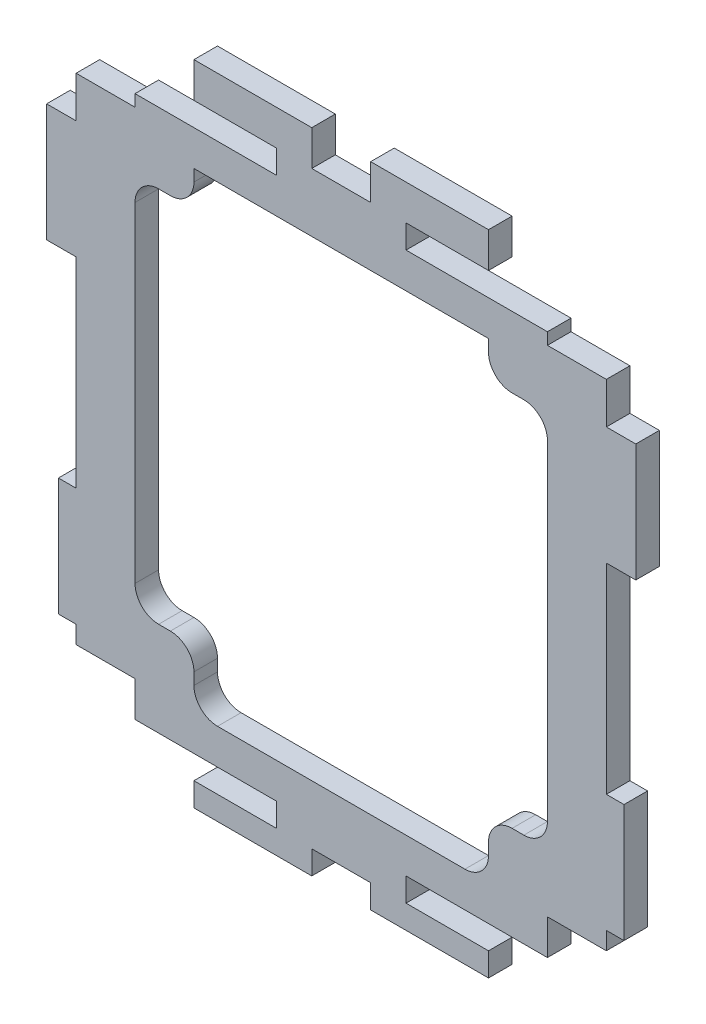
SolidWorks part; units mm, degrees
ref_plane "前视基准面" through (0, 0, 0) normal (0, 0, 1) x (1, 0, 0)
ref_plane "上视基准面" through (0, 0, 0) normal (0, 1, 0) x (1, 0, 0)
ref_plane "右视基准面" through (0, 0, 0) normal (1, 0, 0) x (0, 0, -1)
sketch "Model" plane through (0, 0, 0) normal (0, 0, 1) x (1, 0, 0)
  line L0 (1277.9121, 487.0806) -> (1277.9121, 483.5806)
  line L1 (1277.9121, 446.5806) -> (1277.9121, 445.0806)
  line L2 (1277.9121, 456.5806) -> (1276.4121, 456.5806)
  line L3 (1277.9121, 446.5806) -> (1276.4121, 446.5806)
  line L4 (1277.9121, 445.0806) -> (1282.9121, 445.0806)
  line L5 (1282.9121, 445.0806) -> (1282.9121, 442.0806)
  line L6 (1277.9121, 456.5806) -> (1277.9121, 473.5806)
  line L7 (1277.9121, 487.0806) -> (1282.9121, 487.0806)
  line L8 (1282.9121, 487.0806) -> (1282.9121, 488.0806)
  line L9 (1276.4121, 456.5806) -> (1276.4121, 446.5806)
  line L10 (1302.9121, 490.0806) -> (1297.9121, 490.0806)
  line L11 (1297.9121, 493.0806) -> (1287.9121, 493.0806)
  line L12 (1287.9121, 490.0806) -> (1287.9121, 493.0806)
  line L13 (1297.9121, 493.0806) -> (1297.9121, 490.0806)
  line L14 (1297.9121, 438.0806) -> (1287.9121, 438.0806)
  line L15 (1287.9121, 440.0806) -> (1287.9121, 438.0806)
  line L16 (1297.9121, 438.0806) -> (1297.9121, 440.0806)
  line L17 (1284.9121, 482.0806) -> (1285.9121, 482.0806)
  line L18 (1287.9121, 484.0806) -> (1287.9121, 485.0806)
  line L19 (1284.9121, 450.0806) -> (1285.9121, 450.0806)
  line L20 (1287.9121, 448.0806) -> (1287.9121, 447.0806)
  line L21 (1289.9121, 445.0806) -> (1310.9121, 445.0806)
  line L22 (1322.9121, 487.0806) -> (1322.9121, 483.5806)
  line L23 (1322.9121, 473.5806) -> (1322.9121, 456.5806)
  line L24 (1322.9121, 473.5806) -> (1325.4121, 473.5806)
  line L25 (1322.9121, 483.5806) -> (1325.4121, 483.5806)
  line L26 (1322.9121, 456.5806) -> (1324.4121, 456.5806)
  line L27 (1322.9121, 446.5806) -> (1324.4121, 446.5806)
  line L28 (1322.9121, 445.0806) -> (1317.9121, 445.0806)
  line L29 (1317.9121, 445.0806) -> (1317.9121, 442.0806)
  line L30 (1322.9121, 445.0806) -> (1322.9121, 446.5806)
  line L31 (1322.9121, 487.0806) -> (1317.9121, 487.0806)
  line L32 (1317.9121, 487.0806) -> (1317.9121, 488.0806)
  line L33 (1324.4121, 456.5806) -> (1324.4121, 446.5806)
  line L34 (1312.9121, 490.0806) -> (1312.9121, 493.0806)
  line L35 (1302.9121, 493.0806) -> (1312.9121, 493.0806)
  line L36 (1302.9121, 493.0806) -> (1302.9121, 490.0806)
  line L37 (1302.9121, 438.0806) -> (1312.9121, 438.0806)
  line L38 (1312.9121, 440.0806) -> (1312.9121, 438.0806)
  line L39 (1302.9121, 438.0806) -> (1302.9121, 440.0806)
  line L40 (1315.9121, 482.0806) -> (1314.9121, 482.0806)
  line L41 (1312.9121, 484.0806) -> (1312.9121, 485.0806)
  line L42 (1315.9121, 450.0806) -> (1314.9121, 450.0806)
  line L43 (1312.9121, 448.0806) -> (1312.9121, 447.0806)
  line L44 (1317.9121, 480.0806) -> (1317.9121, 452.0806)
  line L45 (1282.9121, 480.0806) -> (1282.9121, 452.0806)
  line L46 (1277.9121, 483.5806) -> (1275.4121, 483.5806)
  line L47 (1275.4121, 473.5806) -> (1277.9121, 473.5806)
  line L48 (1294.9121, 488.0806) -> (1282.9121, 488.0806)
  line L49 (1305.9121, 488.0806) -> (1317.9121, 488.0806)
  line L50 (1312.9121, 490.0806) -> (1305.9121, 490.0806)
  line L51 (1287.9121, 490.0806) -> (1294.9121, 490.0806)
  line L52 (1282.9121, 442.0806) -> (1294.9121, 442.0806)
  line L53 (1294.9121, 440.0806) -> (1287.9121, 440.0806)
  line L54 (1305.9121, 442.0806) -> (1317.9121, 442.0806)
  line L55 (1312.9121, 440.0806) -> (1305.9121, 440.0806)
  line L56 (1287.9121, 485.0806) -> (1312.9121, 485.0806)
  line L57 (1325.4121, 483.5806) -> (1325.4121, 473.5806)
  line L58 (1294.9121, 488.0806) -> (1294.9121, 490.0806)
  line L59 (1305.9121, 488.0806) -> (1305.9121, 490.0806)
  line L60 (1302.9121, 440.0806) -> (1297.9121, 440.0806)
  line L61 (1294.9121, 442.0806) -> (1294.9121, 440.0806)
  line L62 (1305.9121, 442.0806) -> (1305.9121, 440.0806)
  line L63 (1275.4121, 483.5806) -> (1275.4121, 473.5806)
  arc A0 (1287.9121, 447.0806) -> (1289.9121, 445.0806) centre (1289.9121, 447.0806) ccw
  arc A1 (1284.9121, 482.0806) -> (1282.9121, 480.0806) centre (1284.9121, 480.0806) ccw
  arc A2 (1285.9121, 482.0806) -> (1287.9121, 484.0806) centre (1285.9121, 484.0806) ccw
  arc A3 (1282.9121, 452.0806) -> (1284.9121, 450.0806) centre (1284.9121, 452.0806) ccw
  arc A4 (1287.9121, 448.0806) -> (1285.9121, 450.0806) centre (1285.9121, 448.0806) ccw
  arc A5 (1317.9121, 480.0806) -> (1315.9121, 482.0806) centre (1315.9121, 480.0806) ccw
  arc A6 (1310.9121, 445.0806) -> (1312.9121, 447.0806) centre (1310.9121, 447.0806) ccw
  arc A7 (1312.9121, 484.0806) -> (1314.9121, 482.0806) centre (1314.9121, 484.0806) ccw
  arc A8 (1315.9121, 450.0806) -> (1317.9121, 452.0806) centre (1315.9121, 452.0806) ccw
  arc A9 (1314.9121, 450.0806) -> (1312.9121, 448.0806) centre (1314.9121, 448.0806) ccw
extrude "凸台-拉伸1" add sketch "Model" along normal blind 2
